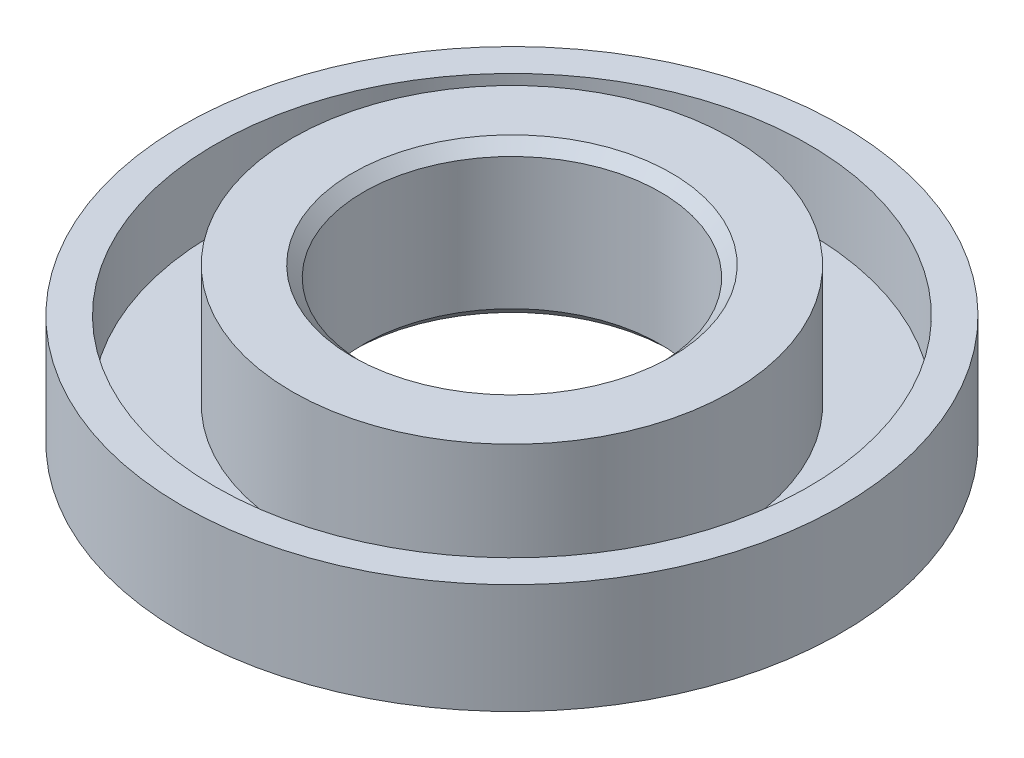
SolidWorks part; units mm, degrees
material "Простая углеродистая сталь"
ref_plane "Спереди" through (0, 0, 0) normal (0, 0, 1) x (1, 0, 0)
ref_plane "Сверху" through (0, 0, 0) normal (0, 1, 0) x (1, 0, 0)
ref_plane "Справа" through (0, 0, 0) normal (1, 0, 0) x (0, 0, -1)
ref_plane "Плоскость4" through (0, 0, 0) normal (0, 0, -1) x (-1, 0, 0)
sketch "Эскиз1" plane through (0, 0, 0) normal (0, 0, -1) x (-1, 0, 0)
  line L0 (-20, 14) -> (-20, 3)
  line L1 (-20, 3) -> (-27, 3)
  line L2 (-27, 3) -> (-27, 10)
  line L3 (-27, 10) -> (-30, 10)
  line L4 (-30, 10) -> (-30, 0)
  line L5 (-30, 0) -> (-14.5, 0)
  line L6 (-14.5, 0) -> (-13.5, 1)
  line L7 (-13.5, 1) -> (-13.5, 13)
  line L8 (-13.5, 13) -> (-14.5, 14)
  line L9 (-14.5, 14) -> (-20, 14)
  line L10 (0, 0) -> (0, 14) construction
revolve "Повернуть1" add sketch "Эскиз1" angle 360 about L10
